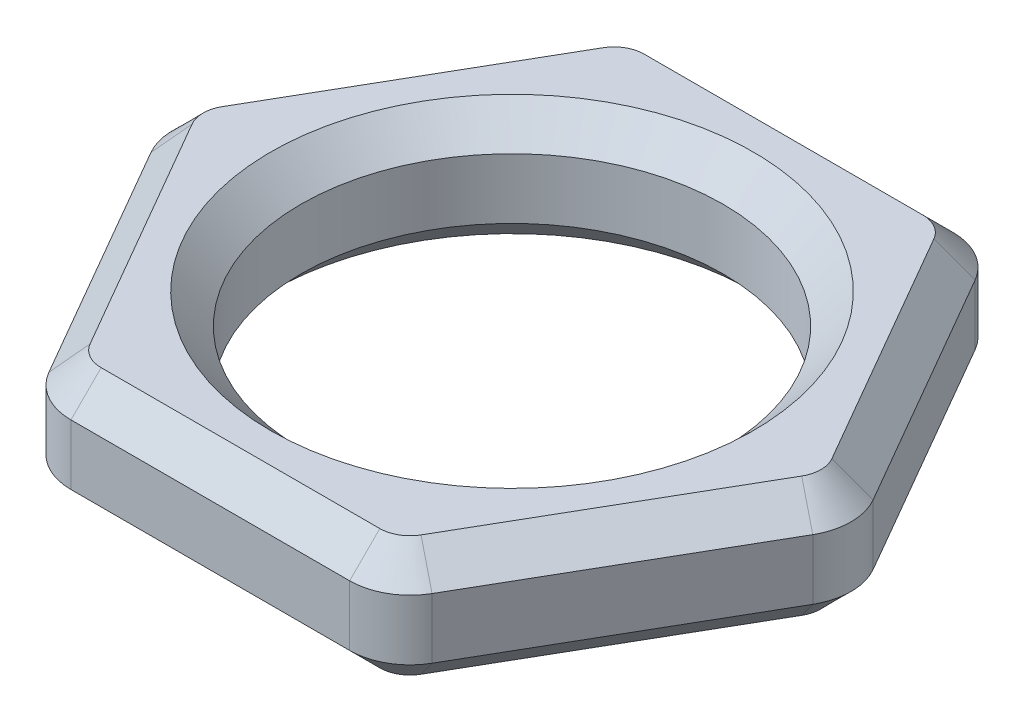
SolidWorks part; units mm, degrees
ref_plane "前视基准面" through (0, 0, 0) normal (0, 0, 1) x (1, 0, 0)
ref_plane "上视基准面" through (0, 0, 0) normal (0, 1, 0) x (1, 0, 0)
ref_plane "右视基准面" through (0, 0, 0) normal (1, 0, 0) x (0, 0, -1)
sketch "草图1" plane through (0, 0, 0) normal (0, 1, 0) x (1, 0, 0)
  line L1 (5.7735, 0) -> (2.8868, 5)
  line L2 (2.8868, 5) -> (-2.8868, 5)
  line L3 (-2.8868, 5) -> (-5.7735, 0)
  line L4 (-5.7735, 0) -> (-2.8868, -5)
  line L5 (-2.8868, -5) -> (2.8868, -5)
  line L6 (2.8868, -5) -> (5.7735, 0)
  circle A0 centre (0, 0) radius 5 construction
  circle A1 centre (0, 0) radius 3.5
  dimension "D2" = 7
  dimension "D1" = 10
extrude "凸台-拉伸1" add sketch "草图1" along normal blind 2
fillet "圆角1" radius 1 6 edges at (-5.7735, 1, 0) (-2.8868, 1, -5) (2.8868, 1, -5) (5.7735, 1, 0) (2.8868, 1, 5) (-2.8868, 1, 5)
chamfer "倒角1" distance 0.5 angle 45 26 edges at (0, 2, 3.5) (0, 2, 5) (-4.3301, 2, 2.5) (-4.3301, 2, -2.5) (0, 2, -5) (4.3301, 2, -2.5) (4.3301, 2, 2.5) (0, 0, 3.5) (4.3301, 0, -2.5) (0, 0, -5) (-4.3301, 0, -2.5) (-4.3301, 0, 2.5) (0, 0, 5) (4.3301, 0, 2.5) (-2.8094, 2, -4.866) (2.8094, 2, -4.866) (5.6188, 2, 0) (2.8094, 2, 4.866) (-2.8094, 2, 4.866) (-5.6188, 2, 0) (-2.8094, 0, 4.866) (2.8094, 0, 4.866) (5.6188, 0, 0) (2.8094, 0, -4.866) (-2.8094, 0, -4.866) (-5.6188, 0, 0)
